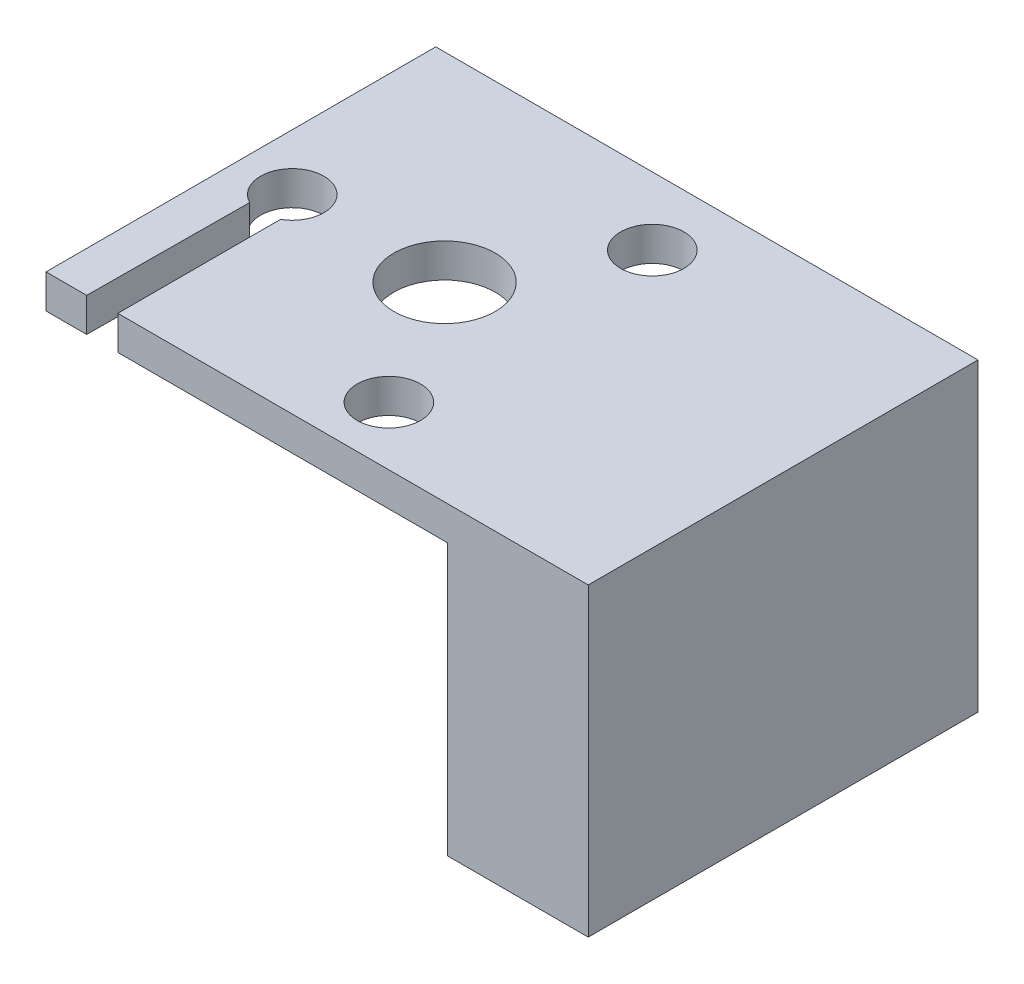
SolidWorks part; units mm, degrees
ref_plane "Front Plane" through (0, 0, 0) normal (0, 0, 1) x (1, 0, 0)
ref_plane "Top Plane" through (0, 0, 0) normal (0, 1, 0) x (1, 0, 0)
ref_plane "Right Plane" through (0, 0, 0) normal (1, 0, 0) x (0, 0, -1)
sketch "Sketch1" plane through (0, 0, 0) normal (0, 1, 0) x (1, 0, 0)
  line L0 (-12.5354, -0.5327) -> (-12.6413, -15.6981)
  line L2 (-9.7257, -15.6981) -> (-9.7257, -0.4581)
  line L3 (-9.7257, -15.6981) -> (34.3487, -15.6981)
  line L4 (34.3487, -15.6981) -> (34.3487, 20.8144)
  line L5 (34.3487, 20.8144) -> (-16.4513, 20.8144)
  line L6 (-16.4513, 20.8144) -> (-16.4513, -15.6981)
  line L7 (-16.4513, -15.6981) -> (-12.6413, -15.6981)
  circle A0 centre (3.0612, 2.1265) radius 4.7485
  arc A1 (-9.7257, -0.4581) -> (-12.5354, -0.5327) centre (-11.1999, 2.1176) ccw
  circle A2 centre (10.1839, 14.4635) radius 2.9678
  circle A3 centre (10.1839, -10.2106) radius 2.9678
  point P8 (3.0612, 2.1265)
  point P10 (0, 0)
  point P18 (-16.4513, -0.2498)
  dimension "D1" = 50.8
  dimension "D2" = 15.24
  dimension "D3" = 15.6981
  dimension "D4" = 16.4513
  dimension "D5" = 3.81
  dimension "D6" = 36.5125
extrude "Boss-Extrude1" add sketch "Sketch1" along normal blind 3.175
sketch "Sketch2" plane through (0, 0, 0) normal (0, -1, 0) x (1, 0, 0)
  line L0 (20.2636, -20.8144) -> (34.3487, -20.8144)
  line L1 (34.3487, -20.8144) -> (-16.4513, -20.8144) construction
  line L2 (34.3487, -20.8144) -> (34.3487, 15.6981)
  line L3 (34.3487, 15.6981) -> (21.1565, 15.6981)
  line L4 (-9.7257, 15.6981) -> (34.3487, 15.6981) construction
  arc A0 (20.2636, -20.8144) -> (21.1565, 15.6981) centre (3.0612, -2.1265) ccw construction
  arc A1 (20.2636, -20.8144) -> (21.1565, 15.6981) centre (3.0612, -2.1265) ccw
  dimension "D1" = 25.4
extrude "Boss-Extrude2" add sketch "Sketch2" along normal blind 25.4
